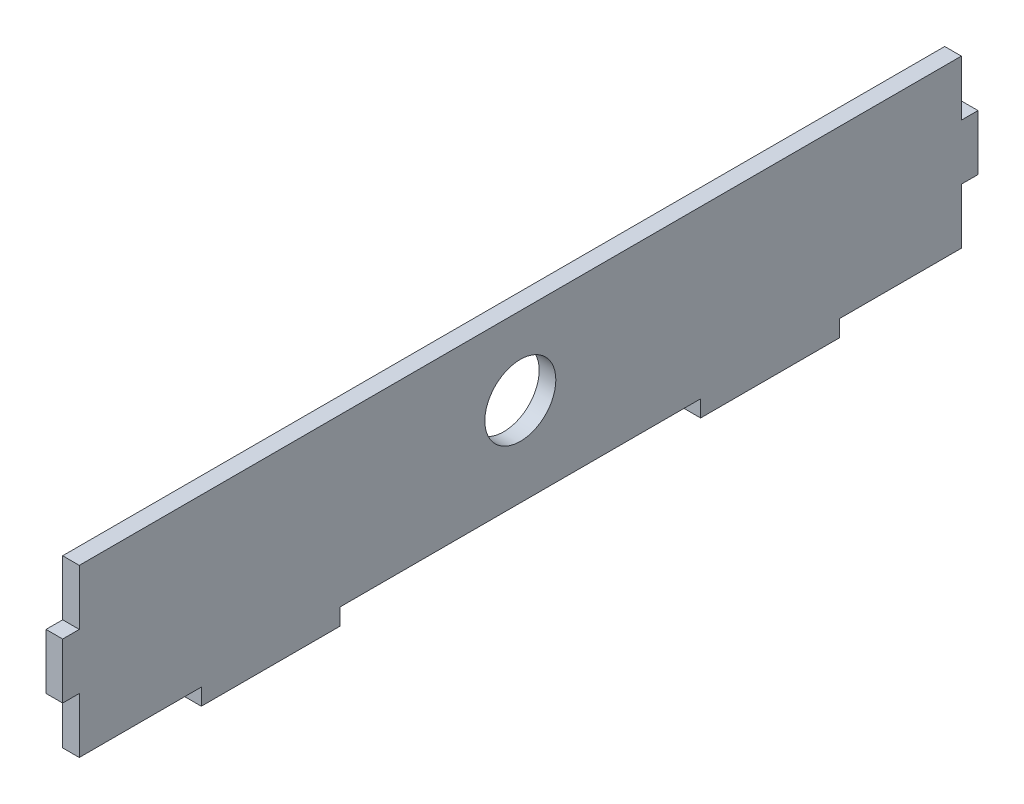
SolidWorks part; units mm, degrees
ref_plane "Front Plane" through (0, 0, 0) normal (0, 0, 1) x (1, 0, 0)
ref_plane "Top Plane" through (0, 0, 0) normal (0, 1, 0) x (1, 0, 0)
ref_plane "Right Plane" through (0, 0, 0) normal (1, 0, 0) x (0, 0, -1)
sketch "Sketch2" plane through (0, 0, 0) normal (1, 0, 0) x (0, 0, -1)
  line L0 (-57.5, -15) -> (-79.5, -15)
  line L1 (79.5, -15) -> (57.5, -15)
  line L2 (79.5, -15) -> (79.5, -5)
  line L3 (79.5, 15) -> (-79.5, 15)
  line L4 (-79.5, -15) -> (-79.5, -5)
  line L5 (79.5, -15) -> (-79.5, 15) construction
  line L6 (79.5, 15) -> (-79.5, -15) construction
  line L7 (-79.5, 5) -> (-82.5, 5)
  line L9 (-79.5, -5) -> (-82.5, -5)
  line L10 (-82.5, 5) -> (-82.5, -5)
  line L11 (32.5, -15) -> (-32.5, -15)
  line L12 (-57.5, -15) -> (-57.5, -18)
  line L13 (-57.5, -18) -> (-32.5, -18)
  line L14 (-32.5, -15) -> (-32.5, -18)
  line L15 (-79.5, 5) -> (-79.5, 15)
  line L16 (32.5, -15) -> (32.5, -18)
  line L17 (32.5, -18) -> (57.5, -18)
  line L18 (57.5, -15) -> (57.5, -18)
  line L19 (79.5, 5) -> (79.5, 15)
  line L27 (79.5, 5) -> (82.5, 5)
  line L29 (79.5, -5) -> (82.5, -5)
  line L30 (82.5, 5) -> (82.5, -5)
  circle A0 centre (0, 1) radius 6.4
  point P0 (0, 0)
  dimension "D11" = 12.8
  dimension "D12" = 16
  dimension "D1" = 159
  dimension "D2" = 25
  dimension "D3" = 3
  dimension "D4" = 3
  dimension "D5" = 10
  dimension "D6" = 30
  dimension "D7" = 10
  dimension "D8" = 65
  dimension "D9" = 22
extrude "Boss-Extrude3" add sketch "Sketch2" along normal blind 3
